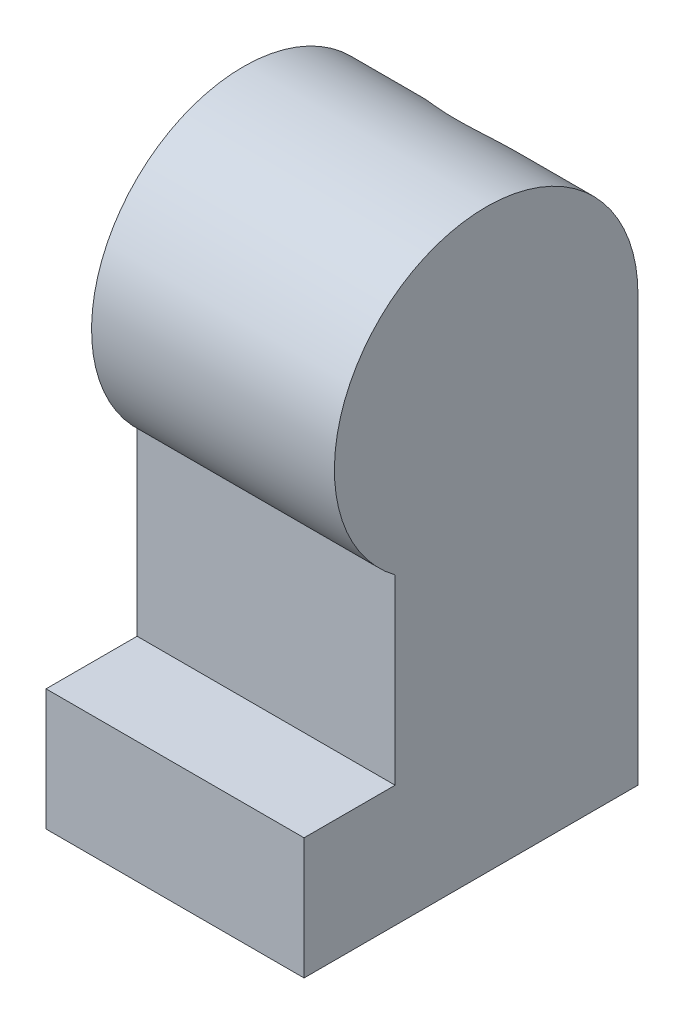
SolidWorks part; units mm, degrees
material "ABS"
ref_plane "Front Plane" through (0, 0, 0) normal (0, 0, 1) x (1, 0, 0)
ref_plane "Top Plane" through (0, 0, 0) normal (0, 1, 0) x (1, 0, 0)
ref_plane "Right Plane" through (0, 0, 0) normal (1, 0, 0) x (0, 0, -1)
sketch "Sketch2" plane through (0, 0, 0) normal (1, 0, 0) x (0, 0, -1)
  line L0 (0, 11.1125) -> (0, 0) construction
  line L1 (-4.3656, 0) -> (4.3656, 0)
  line L2 (-4.3656, 0) -> (-4.3656, 3.175)
  line L3 (-4.3656, 3.175) -> (-1.9844, 3.175)
  line L4 (-1.9844, 3.175) -> (-1.9844, 11.1125)
  line L5 (-1.9844, 11.1125) -> (4.3656, 11.1125)
  line L6 (4.3656, 11.1125) -> (4.3656, 0)
  dimension "D1" = 8.7312
  dimension "D2" = 3.175
  dimension "D3" = 11.1125
  dimension "D4" = 2.3813
extrude "Boss-Extrude4" add sketch "Sketch2" along normal blind 6.7469
sketch "Sketch6" plane through (6.7469, 0, 0) normal (1, 0, 0) x (0, 0, -1)
  line L0 (4.3656, 11.1125) -> (-3.5719, 11.1125) construction
  line L1 (0.3969, 11.1125) -> (0.3969, 15.0813) construction
  circle A0 centre (0.3969, 11.1125) radius 3.9688
  dimension "D1" = 7.9375
  dimension "D2" = 3.9688
extrude "Boss-Extrude5" add sketch "Sketch6" against normal up to surface (6.7469 mm away) up to face at (0, 4.7625, 0.6615)
shell "Shell2" thickness 0.7937
sketch "Sketch7" plane through (0, 0, 0) normal (0, -1, 0) x (1, 0, 0)
  line L0 (5.9531, 3.5719) -> (5.9531, -3.5719) construction
  line L1 (1.1906, -2.3813) -> (5.9531, -2.3812) construction
  line L2 (1.1906, -2.3813) -> (1.1906, 2.3812) construction
  line L3 (1.1906, 2.3812) -> (5.9531, 2.3812) construction
  line L4 (5.9531, -2.3812) -> (5.9531, 2.3812) construction
  line L6 (5.9531, 3.5719) -> (5.9531, 2.3812)
  line L9 (5.9531, 2.3812) -> (1.1906, 2.3812)
  line L10 (0.7937, -3.5719) -> (5.9531, -3.5719)
  line L11 (0.7937, -3.5719) -> (0.7937, 3.5719)
  line L12 (0.7937, 3.5719) -> (5.9531, 3.5719)
  line L14 (1.1906, 2.3812) -> (1.1906, -2.3813)
  line L15 (1.1906, -2.3813) -> (5.9531, -2.3812)
  line L16 (5.9531, -2.3812) -> (5.9531, -3.5719)
  point P4 (5.9531, 0)
  point P17 (1.1906, 0)
  dimension "D1" = 4.7625
extrude "Boss-Extrude6" add sketch "Sketch7" against normal up to next
sketch "Sketch11" plane through (0, 0, 0) normal (-1, 0, 0) x (0, 0, 1)
  circle A0 centre (-0.3969, 11.1125) radius 3.9688
  arc A1 (1.9844, 7.9375) -> (-4.3656, 11.1125) centre (-0.3969, 11.1125) ccw construction
extrude "Cut-Extrude2" cut sketch "Sketch11" against normal offset from surface (0.3969 mm away) 6.35 up to face at (6.7469, 5.0895, 1.0896)
sketch "Sketch13" plane through (6.7469, 0, 0) normal (1, 0, 0) x (0, 0, -1)
  circle A0 centre (0.3969, 11.1125) radius 3.9688
  arc A1 (4.3656, 11.1125) -> (-1.9844, 7.9375) centre (0.3969, 11.1125) ccw construction
extrude "Boss-Extrude11" add sketch "Sketch13" against normal up to surface (6.35 mm away) up to face at (0.3969, 11.1125, -0.3969)
sketch "Sketch14" plane through (0, 0, -4.3656) normal (0, 0, -1) x (-1, 0, 0)
  line L0 (-6.7469, 0) -> (0, 0) construction
  line L1 (-6.7469, 0) -> (-6.7469, 11.1125) construction
  circle A0 centre (-3.5719, 3.9688) radius 2.3813
  circle A1 centre (-3.5719, 11.9062) radius 2.3813
  dimension "D2" = 4.7625
  dimension "D1" = 7.9375
  dimension "D3" = 3.9688
  dimension "D4" = 3.175
extrude "Cut-Extrude3" cut sketch "Sketch14" against normal up to surface (1.9844 mm away) up to face at (3.5719, 3.8377, -2.3813)
sketch "Sketch16" plane through (0, 0, -2.3813) normal (0, 0, -1) x (-1, 0, 0)
  line L0 (-0.3969, 11.1125) -> (-2.7781, 11.1125) construction
  line L2 (-2.7781, 9.6612) -> (-2.7781, 14.1513)
  line L4 (-3.5719, 11.9062) -> (-1.1906, 11.9063) construction
  circle A0 centre (-3.5719, 11.9063) radius 2.3813 construction
  arc A2 (-2.7781, 9.6612) -> (-2.7781, 14.1513) centre (-3.5719, 11.9062) cw
  dimension "D1" = 2.3813
extrude "Cut-Extrude4" cut sketch "Sketch16" against normal blind 3.5719
sketch "Sketch17" plane through (0.3969, 0, 0) normal (-1, 0, 0) x (0, 0, 1)
  circle A0 centre (-0.3969, 11.1125) radius 1.1906
  dimension "D1" = 2.3813
extrude "Cut-Extrude5" cut sketch "Sketch17" against normal blind 2.3813
